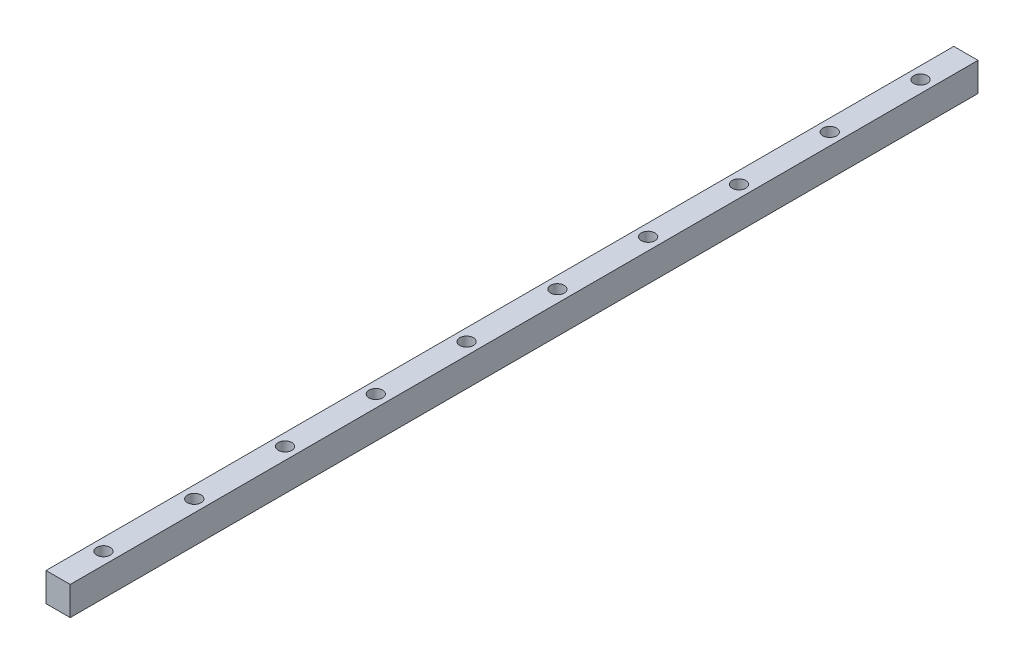
SolidWorks part; units mm, degrees
ref_plane "Front Plane" through (0, 0, 0) normal (0, 0, 1) x (1, 0, 0)
ref_plane "Top Plane" through (0, 0, 0) normal (0, 1, 0) x (1, 0, 0)
ref_plane "Right Plane" through (0, 0, 0) normal (1, 0, 0) x (0, 0, -1)
sketch "Sketch1" plane through (0, 0, 0) normal (0, 0, 1) x (1, 0, 0)
  line L1 (-4, -4.75) -> (4, -4.75)
  line L2 (-4, -4.75) -> (-4, 4.75)
  line L3 (-4, 4.75) -> (4, 4.75)
  line L4 (4, -4.75) -> (4, 4.75)
  line L5 (-4, -4.75) -> (4, 4.75) construction
  line L6 (-4, 4.75) -> (4, -4.75) construction
  point P0 (0, 0)
  dimension "D1" = 8
  dimension "D2" = 9.5
extrude "Boss-Extrude1" add sketch "Sketch1" along normal blind 300
sketch "Sketch2" plane through (0, 4.75, 0) normal (0, 1, 0) x (1, 0, 0)
  line L0 (4, 0) -> (-4, 0) construction
  circle A0 centre (0, -15) radius 2.25
  dimension "D2" = 4.5
  dimension "D1" = 15
extrude "Cut-Extrude1" cut sketch "Sketch2" against normal through all
pattern_linear "LPattern1" count 10 spacing 30 along (0, 0, 1) of "Cut-Extrude1"
